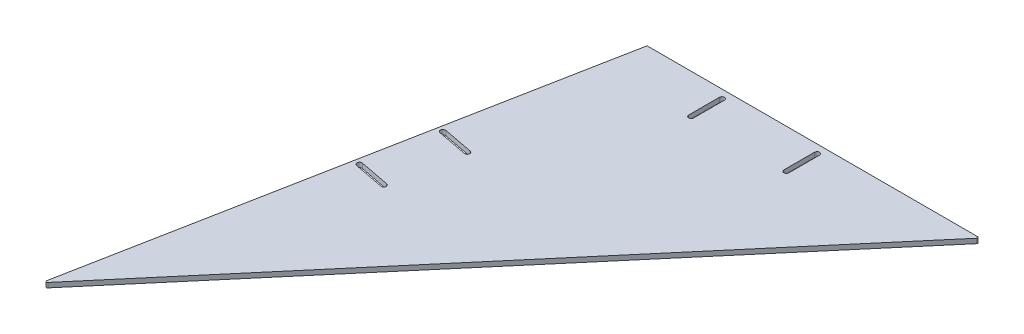
SolidWorks part; units mm, degrees
ref_plane "Front Plane" through (0, 0, 0) normal (1, 0, 0) x (0, 1, 0)
ref_plane "Top Plane" through (0, 0, 0) normal (0, 0, 1) x (0, 1, 0)
ref_plane "Right Plane" through (0, 0, 0) normal (0, 1, 0) x (-1, 0, 0)
sketch "Sketch1" plane through (0, 0, 0) normal (0, 1, 0) x (-1, 0, 0)
  line L0 (0, 0) -> (280, 0)
  line L1 (280, 0) -> (362.0982, 427.1825)
  line L2 (362.0982, 427.1825) -> (0, 0)
  line L3 (210, 32.9) -> (210, 7.1) construction
  line L4 (207.9, 32.9) -> (207.9, 7.1)
  line L5 (212.1, 32.9) -> (212.1, 7.1)
  line L6 (170, 0) -> (170, 40.7655) construction
  line L7 (130, 32.9) -> (130, 7.1) construction
  line L8 (132.1, 32.9) -> (132.1, 7.1)
  line L9 (127.9, 32.9) -> (127.9, 7.1)
  line L10 (278.0632, 153.1172) -> (303.3996, 148.248) construction
  line L11 (277.6669, 151.055) -> (303.0032, 146.1857)
  line L12 (278.4596, 155.1795) -> (303.7959, 150.3102)
  line L13 (313.9717, 176.7652) -> (265.1693, 186.1443) construction
  line L14 (289.3871, 212.039) -> (314.7235, 207.1697) construction
  line L15 (289.7835, 214.1012) -> (315.1198, 209.2319)
  line L16 (288.9908, 209.9767) -> (314.3271, 205.1074)
  arc A0 (207.9, 32.9) -> (212.1, 32.9) centre (210, 32.9) cw
  arc A1 (212.1, 7.1) -> (207.9, 7.1) centre (210, 7.1) cw
  arc A2 (132.1, 32.9) -> (127.9, 32.9) centre (130, 32.9) ccw
  arc A3 (127.9, 7.1) -> (132.1, 7.1) centre (130, 7.1) ccw
  arc A4 (277.6669, 151.055) -> (278.4596, 155.1795) centre (278.0632, 153.1172) cw
  arc A5 (303.7959, 150.3102) -> (303.0032, 146.1857) centre (303.3996, 148.248) cw
  arc A6 (289.7835, 214.1012) -> (288.9908, 209.9767) centre (289.3871, 212.039) ccw
  arc A7 (314.3271, 205.1074) -> (315.1198, 209.2319) centre (314.7235, 207.1697) ccw
  point P6 (210, 20)
  point P15 (130, 20)
  point P22 (290.7314, 150.6826)
  point P31 (302.0553, 209.6043)
  dimension "D5" = 30
  dimension "D6" = 5
  dimension "D1" = 280
  dimension "D2" = 560
  dimension "D3" = 435
  dimension "D4" = 4.2
  dimension "D7" = 70
  dimension "D8" = 40
  dimension "D9" = 5
  dimension "D10" = 30
  dimension "D11" = 180
extrude "Boss-Extrude1" add sketch "Sketch1" along normal blind 4
fillet "Fillet1" radius 1 3 edges at (-362.0982, 2, 427.1825) (0, 2, 0) (-280, 2, 0)
